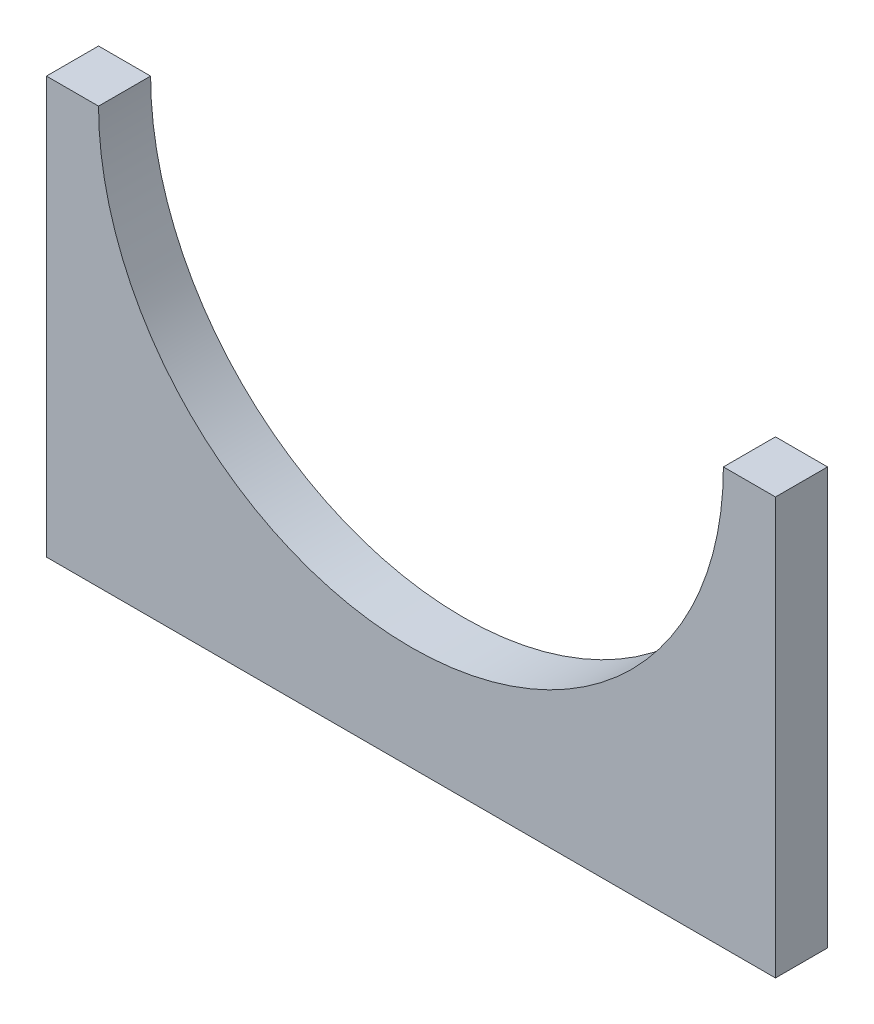
SolidWorks part; units mm, degrees
ref_plane "Front Plane" through (0, 0, 0) normal (0, 0, 1) x (1, 0, 0)
ref_plane "Top Plane" through (0, 0, 0) normal (0, 1, 0) x (1, 0, 0)
ref_plane "Right Plane" through (0, 0, 0) normal (1, 0, 0) x (0, 0, -1)
sketch "Sketch1" plane through (0, 0, 0) normal (0, 0, 1) x (1, 0, 0)
  line L0 (-44.7164, 0) -> (54.8723, 0) construction
  line L1 (-35, 0) -> (-35, -40)
  line L2 (-35, -40) -> (35, -40)
  line L3 (35, -40) -> (35, 0)
  line L4 (0, -24.725) -> (0, -64.725) construction
  line L5 (-35, 0) -> (-30, 0)
  line L6 (30, 0) -> (35, 0)
  arc A0 (-30, 0) -> (30, 0) centre (0, 0) ccw
  point P7 (-35, 0)
  point P8 (35, 0)
  dimension "D1" = 60
  dimension "D3" = 40
  dimension "D2" = 35
extrude "Boss-Extrude1" add sketch "Sketch1" along normal mid plane 5
